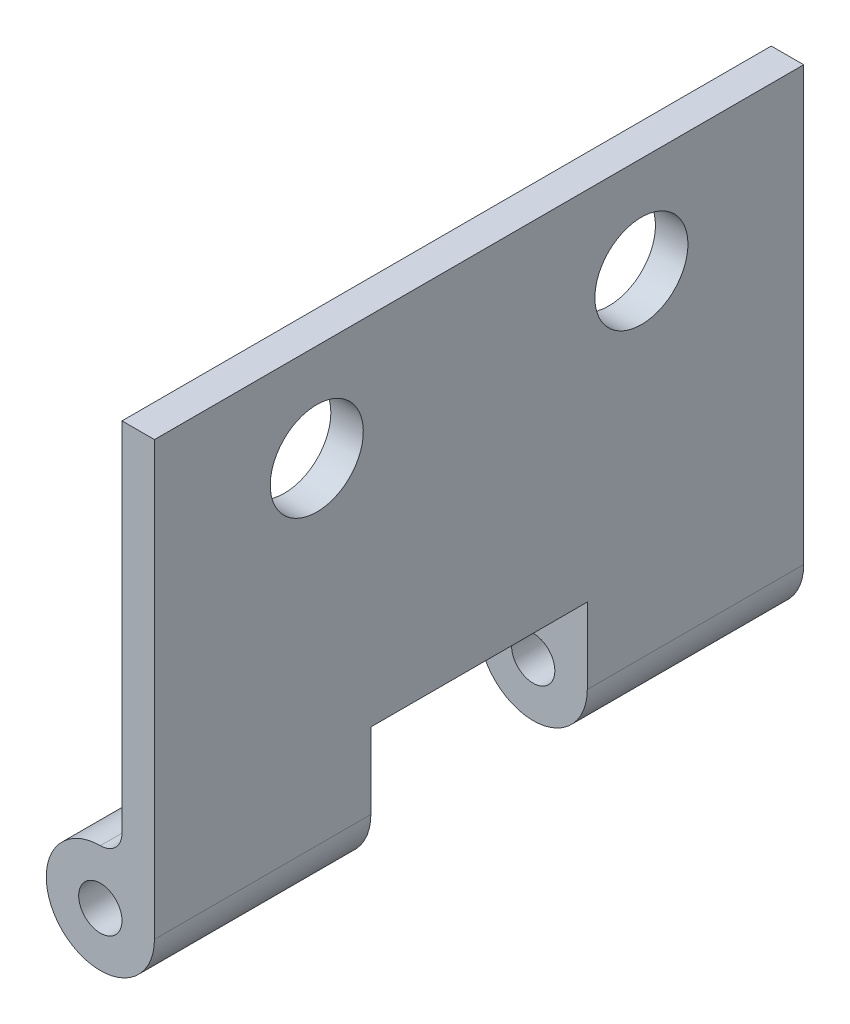
SolidWorks part; units mm, degrees
ref_plane "Front Plane" through (0, 0, 0) normal (0, 0, 1) x (1, 0, 0)
ref_plane "Top Plane" through (0, 0, 0) normal (0, 1, 0) x (1, 0, 0)
ref_plane "Right Plane" through (0, 0, 0) normal (1, 0, 0) x (0, 0, -1)
sketch "Sketch2" plane through (0, 0, 0) normal (0, 0, 1) x (1, 0, 0)
  line L0 (1, 3.5) -> (1, 20)
  line L1 (2.5, 0) -> (2.5, 20)
  line L2 (1, 20) -> (2.5, 20)
  circle A0 centre (0, 0) radius 1
  arc A1 (0, 2.5) -> (2.5, 0) centre (0, 0) ccw
  arc A2 (1, 3.5) -> (0, 2.5) centre (0, 3.5) cw
  dimension "D1" = 2
  dimension "D2" = 5
  dimension "D4" = 1
  dimension "D3" = 20
extrude "Boss-Extrude2" add sketch "Sketch2" along normal blind 30
sketch "Sketch3" plane through (1, 0, 0) normal (-1, 0, 0) x (0, 0, 1)
  line L0 (30, 3.5) -> (0, 3.5) construction
  line L1 (30, 20) -> (30, 3.5) construction
  line L2 (0, 20) -> (0, 3.5) construction
  line L4 (10, -3.5) -> (20, -3.5)
  line L5 (10, -3.5) -> (10, 3.5)
  line L6 (10, 3.5) -> (20, 3.5)
  line L7 (20, -3.5) -> (20, 3.5)
  line L8 (10, -3.5) -> (20, 3.5) construction
  line L9 (10, 3.5) -> (20, -3.5) construction
  circle A0 centre (7.5, 15.5) radius 2.15
  circle A1 centre (22.5, 15.5) radius 2.15
  point P11 (15, 0)
  dimension "D1" = 4.3
  dimension "D2" = 4.3
  dimension "D3" = 15
  dimension "D4" = 7.5
  dimension "D5" = 12
  dimension "D6" = 7.5
  dimension "D7" = 10
  dimension "D8" = 10
  dimension "D9" = 7
extrude "Cut-Extrude1" cut sketch "Sketch3" against normal through all both and the other way through all
